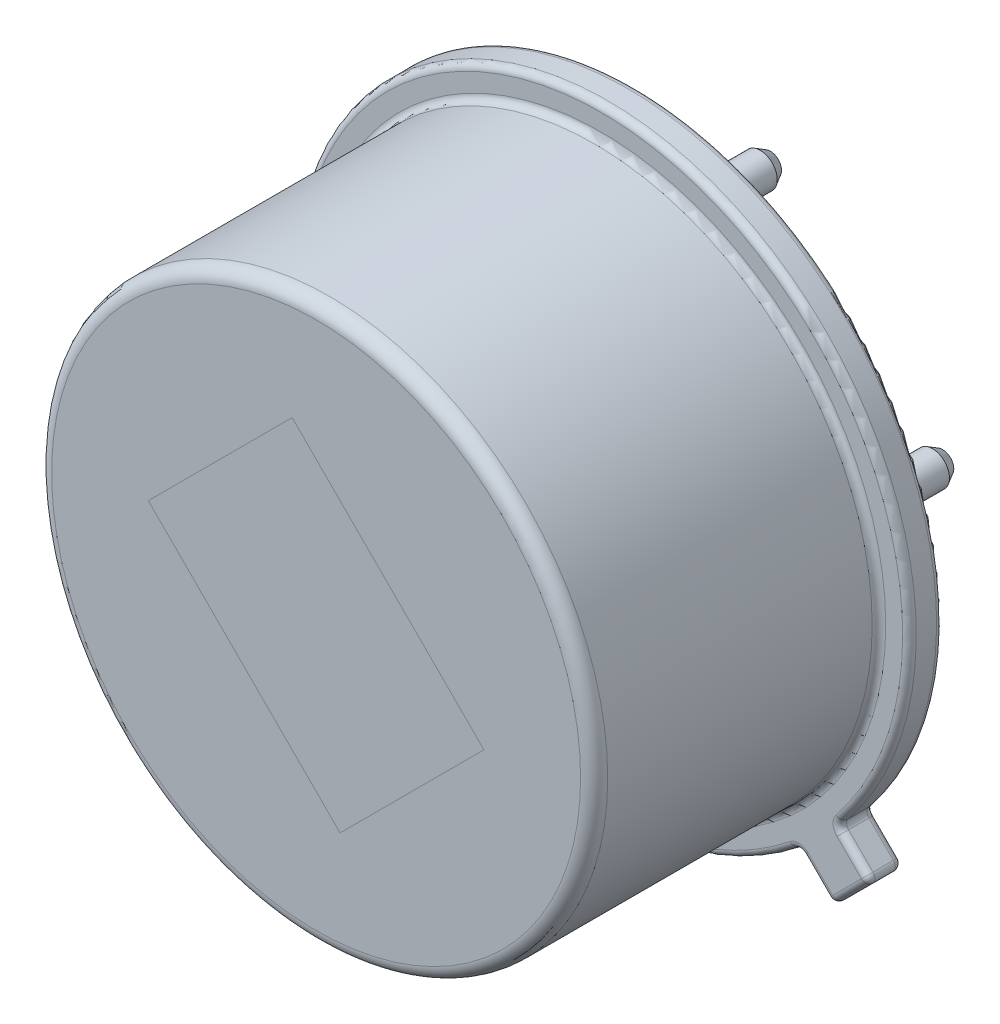
SolidWorks part; units mm, degrees
ref_plane "Front Plane" through (0, 0, 0) normal (0, 0, 1) x (1, 0, 0)
ref_plane "Top Plane" through (0, 0, 0) normal (0, 1, 0) x (1, 0, 0)
ref_plane "Right Plane" through (0, 0, 0) normal (1, 0, 0) x (0, 0, -1)
sketch "Sketch1" plane through (0, 0, 0) normal (0, 0, 1) x (1, 0, 0)
  line L0 (0, 0) -> (6.5502, 0) construction
  line L1 (0, 0) -> (3.6999, -3.6999) construction
  line L2 (3.9827, -3.417) -> (3.417, -3.9827)
  line L3 (3.9827, -3.417) -> (3.4877, -2.922)
  line L4 (3.417, -3.9827) -> (2.922, -3.4877)
  arc A0 (3.4877, -2.922) -> (2.922, -3.4877) centre (0, 0) ccw
  dimension "D1" = 45
  dimension "D2" = 9.1
  dimension "D3" = 0.8
  dimension "D4" = 0.7
extrude "Extrude1" add sketch "Sketch1" along normal blind 0.5
sketch "Sketch2" plane through (0, 0, 0.5) normal (0, 0, 1) x (1, 0, 0)
  circle A0 centre (0, 0) radius 4.1
  dimension "D1" = 8.2
extrude "Extrude2" add sketch "Sketch2" along normal blind 4.2
sketch "Sketch3" plane through (0, 0, 4.7) normal (0, 0, 1) x (1, 0, 0)
  line L0 (0, 0) -> (4.1, 0) construction
  line L1 (0, 0) -> (2.8991, -2.8991) construction
  line L2 (-2.4749, 0.3536) -> (0.3536, -2.4749)
  line L3 (-2.4749, 0.3536) -> (-0.3536, 2.4749)
  line L4 (0.3536, -2.4749) -> (2.4749, -0.3536)
  line L5 (-0.3536, 2.4749) -> (2.4749, -0.3536)
  line L6 (-2.4749, 0.3536) -> (2.4749, -0.3536) construction
  line L7 (0.3536, -2.4749) -> (-0.3536, 2.4749) construction
  circle A0 centre (0, 0) radius 4.1 construction
  dimension "D1" = 45
  dimension "D2" = 4
  dimension "D3" = 3
extrude "Extrude3" cut sketch "Sketch3" against normal blind 0.9
sketch "Sketch4" plane through (0, 0, 0) normal (0, 0, -1) x (-1, 0, 0)
  line L0 (-4.55, 0) -> (4.55, 0) construction
  line L1 (0, 4.55) -> (0, -4.55) construction
  arc A0 (-2.922, -3.4877) -> (-3.4877, -2.922) centre (0, 0) ccw construction
  circle A1 centre (-2.54, 0) radius 0.25
  circle A2 centre (0, 2.54) radius 0.25
  circle A3 centre (2.54, 0) radius 0.25
  dimension "D1" = 0.5
  dimension "D2" = 2.54
  dimension "D3" = 2.54
  dimension "D4" = 2.54
extrude "Extrude4" add sketch "Sketch4" along normal blind 2
sketch "Sketch5" plane through (0, 0, 3.8) normal (0, 0, 1) x (1, 0, 0)
  line L0 (-0.3536, 2.4749) -> (2.4749, -0.3536)
  line L1 (2.4749, -0.3536) -> (0.3536, -2.4749)
  line L2 (0.3536, -2.4749) -> (-2.4749, 0.3536)
  line L3 (-2.4749, 0.3536) -> (-0.3536, 2.4749)
extrude "Extrude5" add sketch "Sketch5" along normal blind 0.9 separate body
fillet "Fillet1" radius 0.2 1 edges at (4.1, 0, 4.7)
fillet "Fillet2" radius 0.1 14 edges at (-2.29, 0, 0) (-3.2173, 3.2173, 0) (3.1695, -3.7352, 0) (3.6999, -3.6999, 0) (3.7352, -3.1695, 0) (4.1, 0, 0.5) (3.6999, -3.6999, 0.5) (3.1695, -3.7352, 0.5) (-3.2173, 3.2173, 0.5) (3.7352, -3.1695, 0.5) (2.922, -3.4877, 0.25) (3.417, -3.9827, 0.25) (3.9827, -3.417, 0.25) (3.4877, -2.922, 0.25)
chamfer "Chamfer1" distance 0.15 angle 30 3 edges at (-2.79, 0, -2) (-0.25, 2.54, -2) (2.29, 0, -2)
sketch "Эскиз1" plane through (0, 0, 0) normal (0, 0, -1) x (-1, 0, 0)
  circle A0 centre (0, 2.54) radius 0.8
  circle A1 centre (0, 2.54) radius 0.25
  circle A2 centre (-2.54, 0) radius 0.8
  circle A3 centre (-2.54, 0) radius 0.25
  circle A4 centre (-2.54, 0) radius 0.25 construction
  circle A5 centre (0, 2.54) radius 0.25 construction
  dimension "D1" = 1.6
extrude "Вырез-Вытянуть1" cut sketch "Эскиз1" against normal blind 0.01
